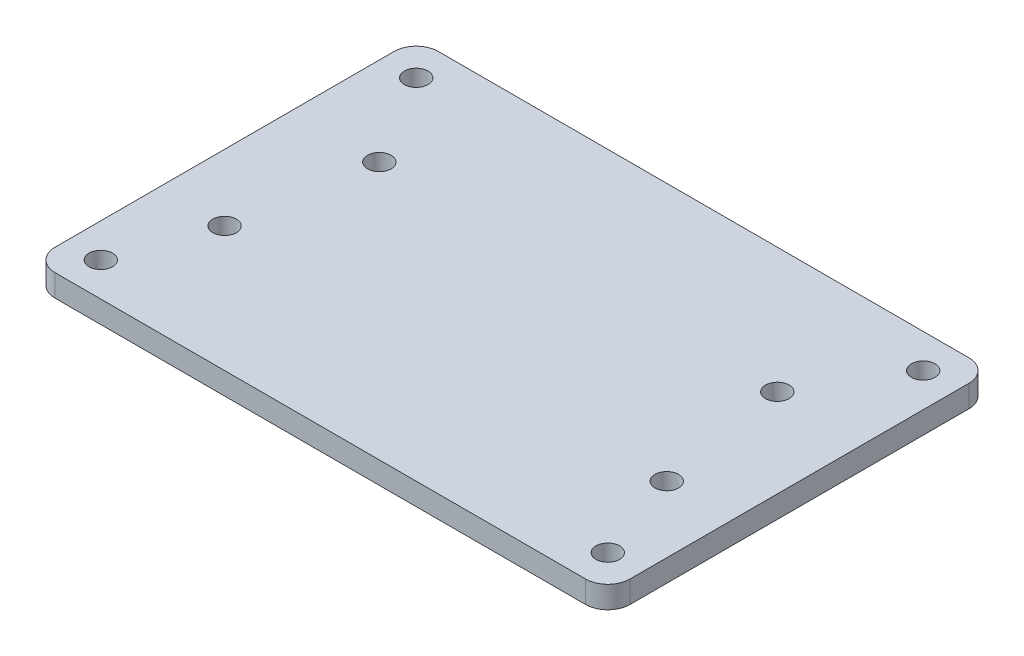
SolidWorks part; units mm, degrees
ref_plane "前视基准面" through (0, 0, 0) normal (0, 0, 1) x (1, 0, 0)
ref_plane "上视基准面" through (0, 0, 0) normal (0, 1, 0) x (1, 0, 0)
ref_plane "右视基准面" through (0, 0, 0) normal (1, 0, 0) x (0, 0, -1)
other "Configuration Table"
sketch "草图1" plane through (0, 0, 0) normal (0, 1, 0) x (1, 0, 0)
  line L1 (-39, -26) -> (39, -26)
  line L2 (-39, -26) -> (-39, 26)
  line L3 (-39, 26) -> (39, 26)
  line L4 (39, -26) -> (39, 26)
  line L5 (-39, -26) -> (39, 26) construction
  line L6 (-39, 26) -> (39, -26) construction
  point P0 (0, 0)
extrude "凸台-拉伸1" add sketch "草图1" along normal blind 3
sketch "草图2" plane through (0, 3, 0) normal (0, 1, 0) x (1, 0, 0)
  line L1 (39, 26) -> (34.4, 26)
  line L2 (39, 26) -> (39, 21.4)
  line L3 (39, 21.4) -> (34.4, 21.4)
  line L4 (34.4, 26) -> (34.4, 21.4)
  line L5 (-39, 26) -> (-34.4, 26)
  line L6 (-39, 26) -> (-39, 21.4)
  line L7 (-39, 21.4) -> (-34.4, 21.4)
  line L8 (-34.4, 26) -> (-34.4, 21.4)
  line L9 (-39, -26) -> (-34.4, -26)
  line L10 (-39, -26) -> (-39, -21.4)
  line L11 (-39, -21.4) -> (-34.4, -21.4)
  line L12 (-34.4, -26) -> (-34.4, -21.4)
  line L13 (39, -26) -> (34.4, -26)
  line L14 (39, -26) -> (39, -21.4)
  line L15 (39, -21.4) -> (34.4, -21.4)
  line L16 (34.4, -26) -> (34.4, -21.4)
  circle A0 centre (-34.4, 21.4) radius 1.6
  circle A1 centre (-34.4, -21.4) radius 1.6
  circle A2 centre (34.4, 21.4) radius 1.6
  circle A3 centre (34.4, -21.4) radius 1.6
extrude "切除-拉伸1" cut sketch "草图2" against normal blind 3 contours L8 A0 L7 | L7 A0 L8 | L3 A2 L4 | L4 A2 L3 | L16 A3 L15 | L15 A3 L16 | A1
sketch "草图7" plane through (0, 3, 0) normal (0, 1, 0) x (1, 0, 0)
  line L0 (-27, 9) -> (27, 9)
  line L1 (-27, 9) -> (-30, -9)
  line L2 (0, 9) -> (0, 26)
  line L3 (30, -9) -> (27, 9)
  line L4 (39, 26) -> (-39, 26) construction
  circle A0 centre (-30, -9) radius 1.6
  circle A1 centre (-27, 9) radius 1.6
  circle A2 centre (27, 9) radius 1.6
  circle A3 centre (30, -9) radius 1.6
extrude "切除-拉伸2" cut sketch "草图7" against normal blind 3
fillet "圆角1" radius 3 4 edges at (-39, 1.5, -26) (-39, 1.5, 26) (39, 1.5, 26) (39, 1.5, -26)
